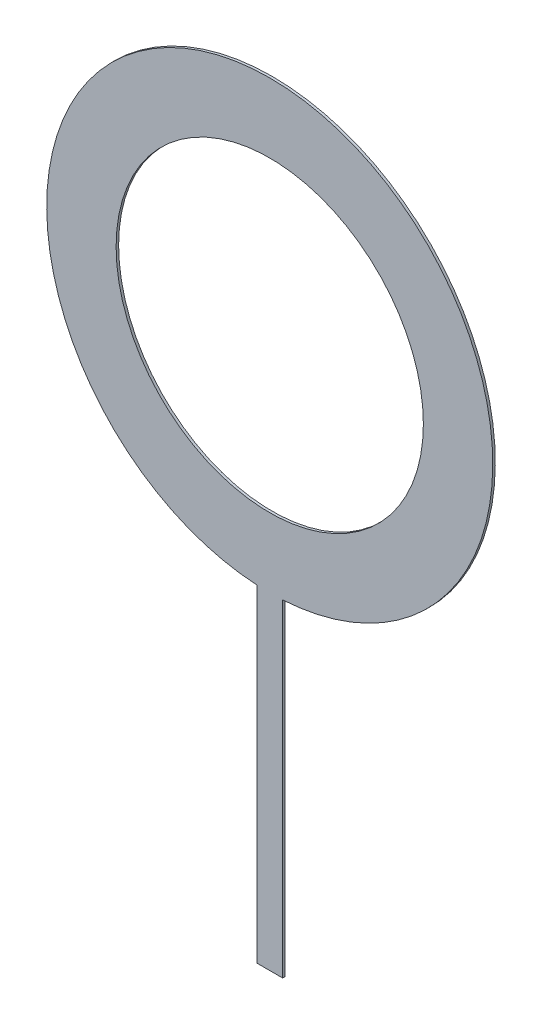
SolidWorks part; units mm, degrees
ref_plane "Front" through (0, 0, 0) normal (0, 0, 1) x (1, 0, 0)
ref_plane "Top" through (0, 0, 0) normal (0, 1, 0) x (1, 0, 0)
ref_plane "Right" through (0, 0, 0) normal (1, 0, 0) x (0, 0, -1)
sketch "Sketch1" plane through (0, 0, 0) normal (0, 0, 1) x (1, 0, 0)
  line L0 (0, -7.75) -> (0, -27.75)
  line L2 (-0.65, -27.75) -> (0.65, -27.75)
  line L3 (-0.65, -27.75) -> (-0.65, -7.75)
  line L4 (-0.65, -7.75) -> (0.65, -7.75)
  line L5 (0.65, -27.75) -> (0.65, -7.75)
  circle A0 centre (0, 0) radius 11.25
  circle A1 centre (0, 0) radius 7.75
  point P10 (0, -7.75)
  point P13 (0, -27.75)
  dimension "D1" = 22.5
  dimension "D2" = 15.5
  dimension "D3" = 1.3
  dimension "D4" = 20
extrude "Boss-Extrude1" add sketch "Sketch1" along normal blind 0.127 contours L4 A1 L5 A0 L3 | L0 A0 L5 L4 | L3 A0 L0 L4 | A0 L3 L2 L0 | A0 L0 L2 L5
